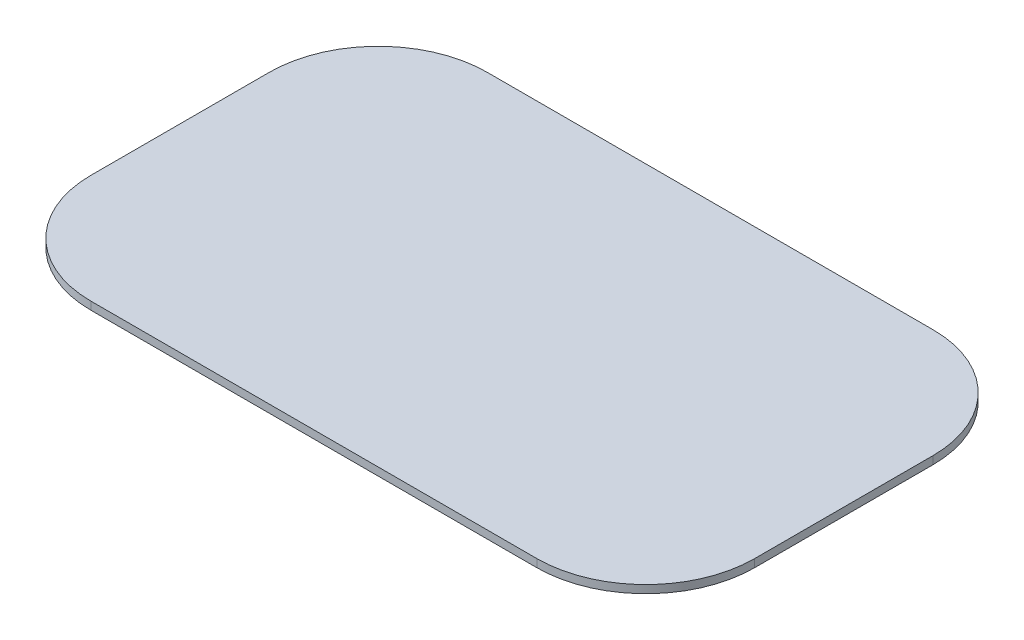
SolidWorks part; units mm, degrees
ref_plane "Front Plane" through (0, 0, 0) normal (0, 0, 1) x (1, 0, 0)
ref_plane "Top Plane" through (0, 0, 0) normal (0, 1, 0) x (1, 0, 0)
ref_plane "Right Plane" through (0, 0, 0) normal (1, 0, 0) x (0, 0, -1)
sketch "Sketch1" plane through (0, 0, 0) normal (0, 1, 0) x (1, 0, 0)
  line L1 (55, 0) -> (280, 0)
  line L2 (0, 55) -> (0, 145)
  line L3 (55, 200) -> (280, 200)
  line L4 (335, 55) -> (335, 145)
  arc A0 (55, 0) -> (0, 55) centre (55, 55) cw
  arc A1 (280, 0) -> (335, 55) centre (280, 55) ccw
  arc A2 (280, 200) -> (335, 145) centre (280, 145) cw
  arc A3 (0, 145) -> (55, 200) centre (55, 145) cw
  point P7 (0, 0)
  point P12 (335, 200)
  point P15 (0, 200)
  dimension "D3" = 55
  dimension "D1" = 335
  dimension "D2" = 200
extrude "Boss-Extrude1" add sketch "Sketch1" along normal blind 4
